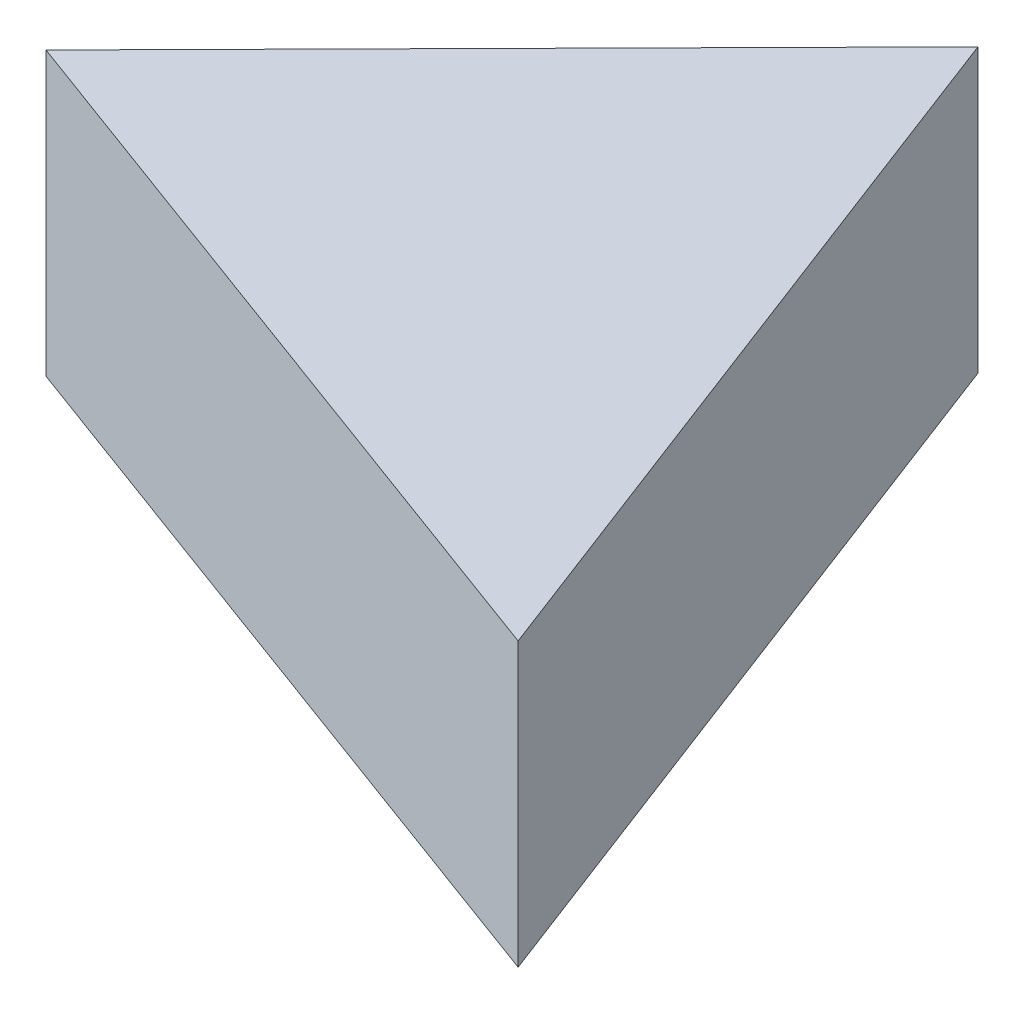
SolidWorks part; units mm, degrees
ref_plane "Front" through (0, 0, 0) normal (0, 0, 1) x (1, 0, 0)
ref_plane "Top" through (0, 0, 0) normal (0, 1, 0) x (1, 0, 0)
ref_plane "Right" through (0, 0, 0) normal (1, 0, 0) x (0, 0, -1)
sketch "Sketch1" plane through (0, 0, 0) normal (0, 1, 0) x (1, 0, 0)
  line L0 (12.1271, 33.3788) -> (-43.6154, -23.0313)
  line L1 (-43.6154, -23.0313) -> (46.3749, -56.2102)
  line L2 (46.3749, -56.2102) -> (12.1271, 33.3788)
extrude "Extrude1" add sketch "Sketch1" along normal blind 34
